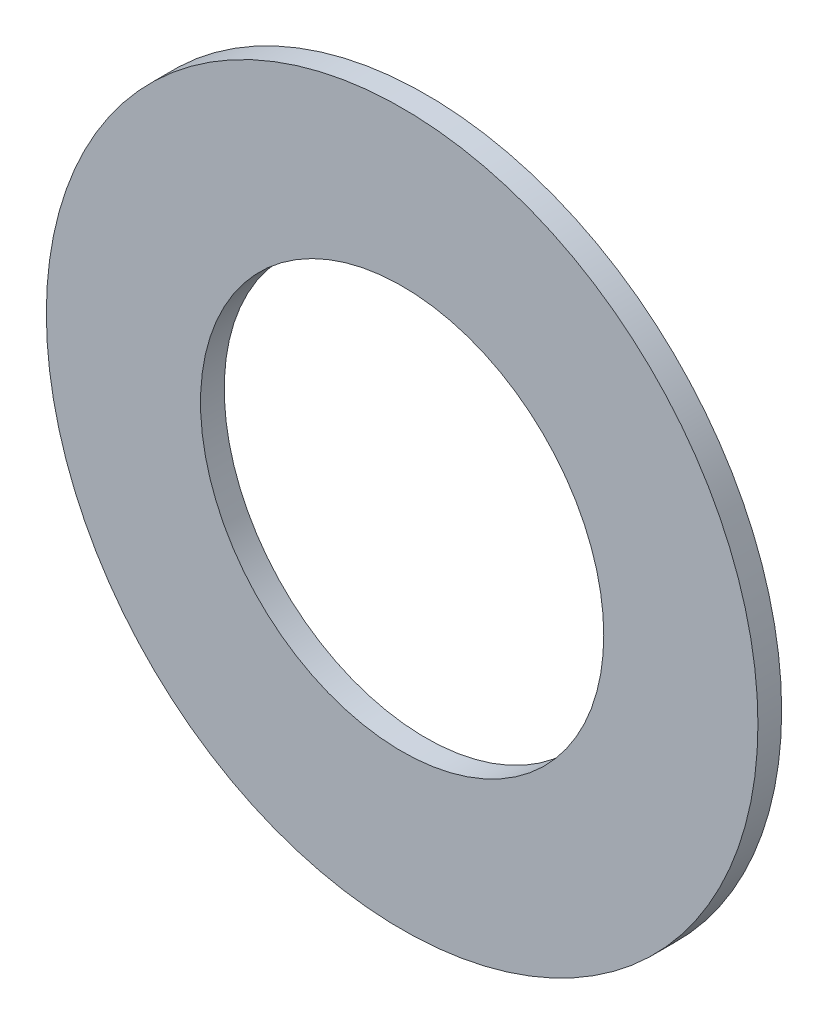
SolidWorks part; units mm, degrees
ref_plane "Plan de face" through (0, 0, 0) normal (0, 0, 1) x (1, 0, 0)
ref_plane "Plan de dessus" through (0, 0, 0) normal (0, 1, 0) x (1, 0, 0)
ref_plane "Plan de droite" through (0, 0, 0) normal (1, 0, 0) x (0, 0, -1)
sketch "Esquisse1" plane through (0, 0, 0) normal (0, 0, 1) x (1, 0, 0)
  circle A0 centre (0, 0) radius 15
  circle A1 centre (0, 0) radius 8.5
  dimension "D1" = 30
  dimension "D2" = 17
extrude "Boss.-Extru.1" add sketch "Esquisse1" along normal blind 1
